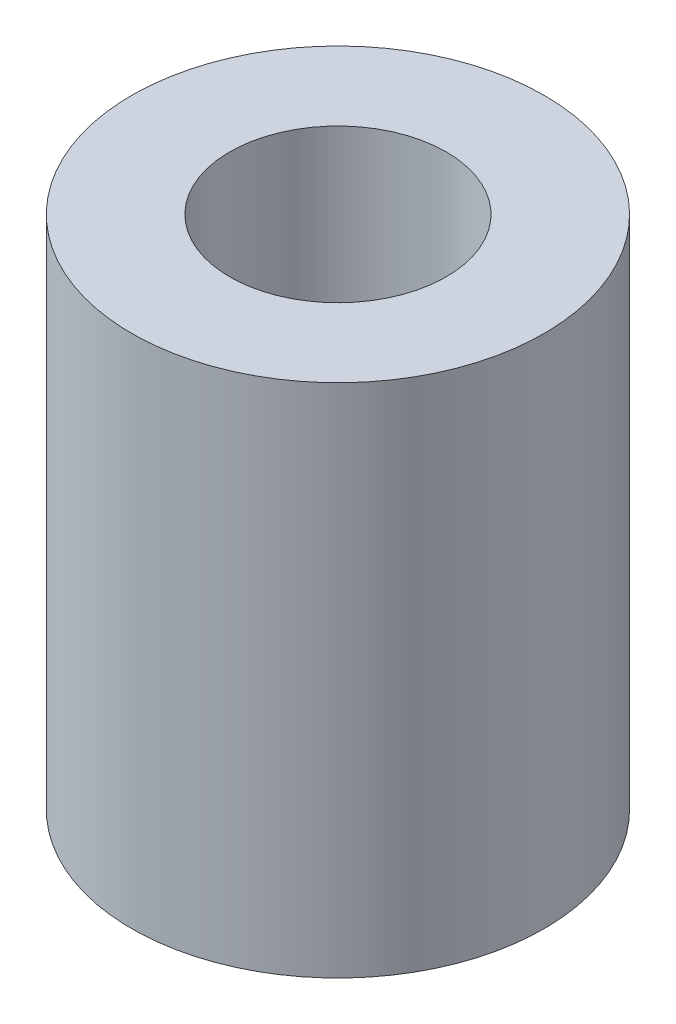
SolidWorks part; units mm, degrees
ref_plane "Plan de face" through (0, 0, 0) normal (0, 0, 1) x (1, 0, 0)
ref_plane "Plan de dessus" through (0, 0, 0) normal (0, 1, 0) x (1, 0, 0)
ref_plane "Plan de droite" through (0, 0, 0) normal (1, 0, 0) x (0, 0, -1)
sketch "Esquisse1" plane through (0, 0, 0) normal (0, 0, 1) x (1, 0, 0)
  line L0 (-2.1, 0) -> (-2.1, 10)
  line L1 (-2.1, 10) -> (-4, 10)
  line L2 (-4, 10) -> (-4, 0)
  line L3 (-4, 0) -> (-2.1, 0)
  line L4 (0, 0) -> (0, 11.8397) construction
  dimension "D1" = 2.1
  dimension "D2" = 10
  dimension "D3" = 4
revolve "Révolution1" add sketch "Esquisse1" angle 360 about L4
